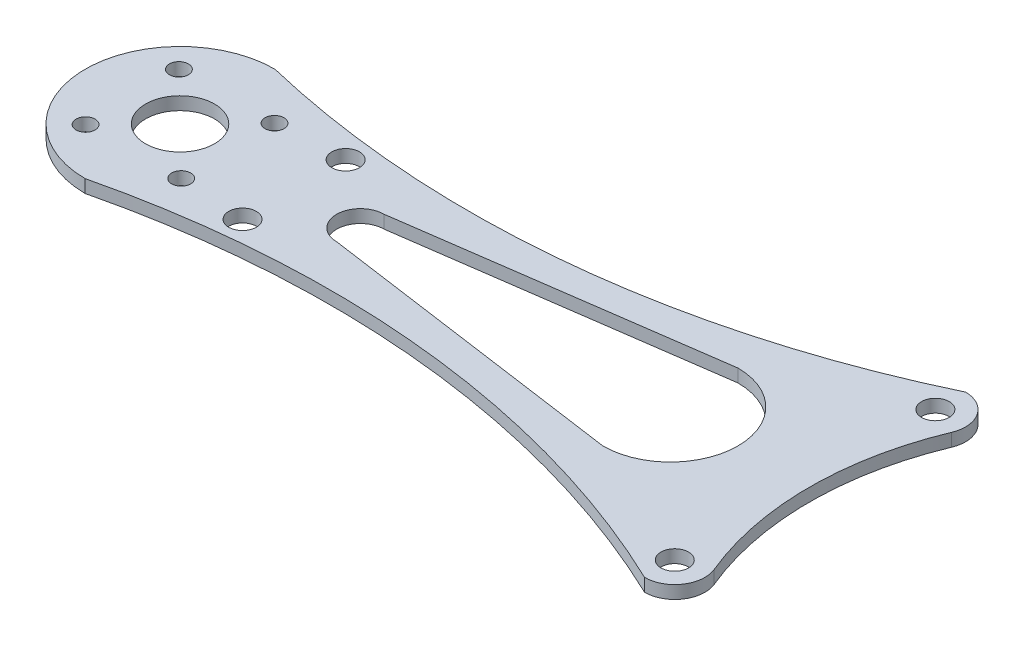
SolidWorks part; units mm, degrees
material "ABS"
ref_plane "Plano frontal" through (0, 0, 0) normal (0, 0, 1) x (1, 0, 0)
ref_plane "Plano superior" through (0, 0, 0) normal (0, 1, 0) x (1, 0, 0)
ref_plane "Plano direito" through (0, 0, 0) normal (1, 0, 0) x (0, 0, -1)
sketch "Esboço1" plane through (0, 0, 0) normal (0, 1, 0) x (1, 0, 0)
  line L0 (0, 43) -> (0, -43) construction
  line L1 (0, -43) -> (43, 0) construction
  line L2 (43, 0) -> (0, 43) construction
  line L3 (0, 43) -> (-43, 0) construction
  line L4 (-43, 0) -> (0, -43) construction
  line L5 (-43, 0) -> (43, 0) construction
  line L6 (0, 0) -> (-39.7268, 16.4554) construction
  line L7 (0, 0) -> (-39.7268, -16.4554) construction
  circle A0 centre (0, 0) radius 43 construction
  arc A1 (-33.2597, 13.7766) -> (-33.2597, -13.7766) centre (0, 0) ccw
  arc A2 (-109, 11) -> (-109, -11) centre (-109, 0) ccw
  circle A3 centre (-36.4932, 15.116) radius 1.6
  circle A4 centre (-36.4932, -15.116) radius 1.6
  arc A5 (-33.2597, 13.7766) -> (-36.4932, 18.616) centre (-36.4932, 15.116) ccw
  circle A6 centre (-95.79, 6) radius 1.6
  arc A7 (-109, 11) -> (-36.4932, 18.616) centre (-83.4775, 116.9698) ccw
  arc A8 (-109, -11) -> (-36.4932, -18.616) centre (-83.4775, -116.9698) cw
  circle A9 centre (-95.79, -5.96) radius 1.6
  arc A10 (-36.4932, -18.616) -> (-33.2597, -13.7766) centre (-36.4932, -15.116) ccw
  dimension "D1" = 86
  dimension "D4" = 7
  dimension "D5" = 22
  dimension "D9" = 3.2
  dimension "D10" = 7
  dimension "D11" = 109
  dimension "D7" = 3.2
  dimension "D8" = 13.21
  dimension "D12" = 11.96
  dimension "D13" = 6
  dimension "D2" = 22.5
  dimension "D3" = 22.5
  dimension "D6" = 109
extrude "Ressalto-extrusão1" add sketch "Esboço1" along normal mid plane 1.5
sketch "Esboço2" plane through (0, 0.75, 0) normal (0, 1, 0) x (1, 0, 0)
  line L0 (-88.0784, 2.7576) -> (-52.1196, 7.8315)
  line L1 (-114.5459, 5.4134) -> (-103.5866, 5.5459) construction
  line L2 (-88.0784, -2.7576) -> (-52.1196, -7.8315)
  line L3 (-103.5866, 5.5459) -> (-103.4541, -5.4134) construction
  line L4 (-103.4541, -5.4134) -> (-114.4134, -5.5459) construction
  line L5 (-114.4134, -5.5459) -> (-114.5459, 5.4134) construction
  arc A0 (-52.1196, -7.8315) -> (-52.1196, 7.8315) centre (-52.1196, 0) ccw
  arc A1 (-88.0784, 2.7576) -> (-88.0784, -2.7576) centre (-88.0784, 0) ccw
  circle A2 centre (-109, 0) radius 4
  arc A3 (-109, 11) -> (-109, -11) centre (-109, 0) ccw construction
  circle A4 centre (-103.5866, 5.5459) radius 1.1
  circle A5 centre (-103.4541, -5.4134) radius 1.1
  circle A6 centre (-114.4134, -5.5459) radius 1.1
  circle A7 centre (-114.5459, 5.4134) radius 1.1
  point P7 (-120, 0)
  point P26 (-109, 0)
  dimension "D1" = 7.8315
  dimension "D2" = 2.7576
  dimension "D6" = 8
  dimension "D7" = 11
  dimension "D8" = 2.2
  dimension "D3" = 18.86
  dimension "D4" = 54.8188
  dimension "D5" = 13.7766
  dimension "D10" = 7.75
  dimension "D11" = 70.1944
  dimension "D12" = 70.3269
  dimension "D13" = 81.1538
  dimension "D9" = 4
extrude "Corte-extrusão1" cut sketch "Esboço2" against normal up to next
